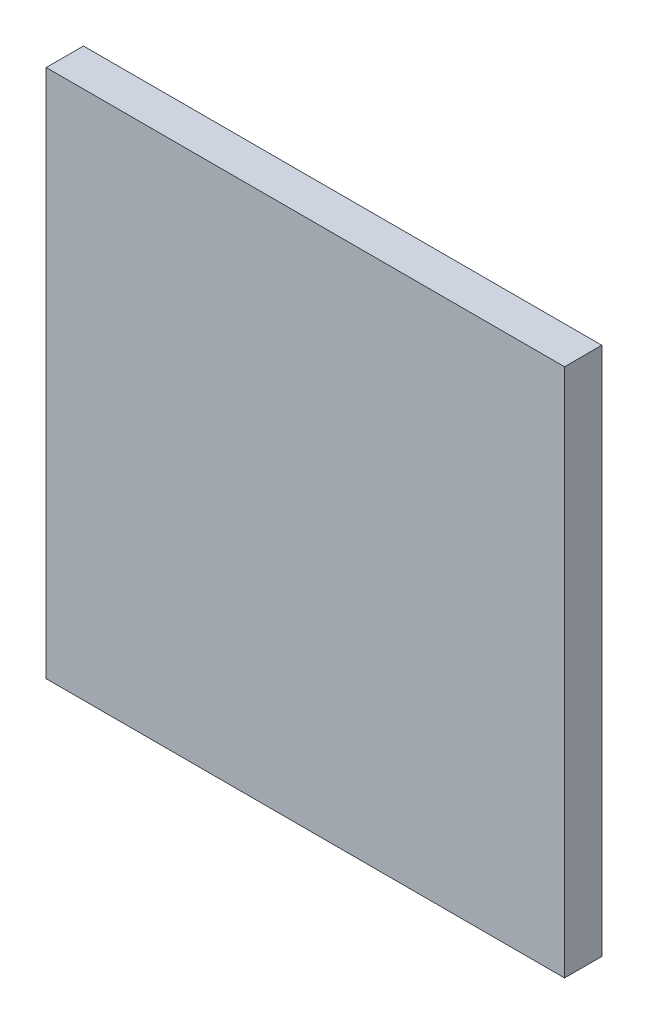
SolidWorks part; units mm, degrees
ref_plane "Front Plane" through (0, 0, 0) normal (0, 0, 1) x (1, 0, 0)
ref_plane "Top Plane" through (0, 0, 0) normal (0, 1, 0) x (1, 0, 0)
ref_plane "Right Plane" through (0, 0, 0) normal (1, 0, 0) x (0, 0, -1)
sketch "Sketch1" plane through (0, 0, 0) normal (0, 0, 1) x (1, 0, 0)
  line L0 (-8, 9.09) -> (8, 9.09)
  line L1 (8, 9.09) -> (8, -7.25)
  line L2 (8, -7.25) -> (-8, -7.25)
  line L3 (-8, -7.25) -> (-8, 9.09)
extrude "Component_Outline" add sketch "Sketch1" along normal blind 1.15 separate body
sketch3d "3DSketch1"
  line L0 (0, 0, 0) -> (1, 0, 0)
  line L1 (0, 0, 0) -> (0, 1, 0)
  line L2 (0, 0, 0) -> (0, 0, 1)
  point P0 (0, 0, 0)
